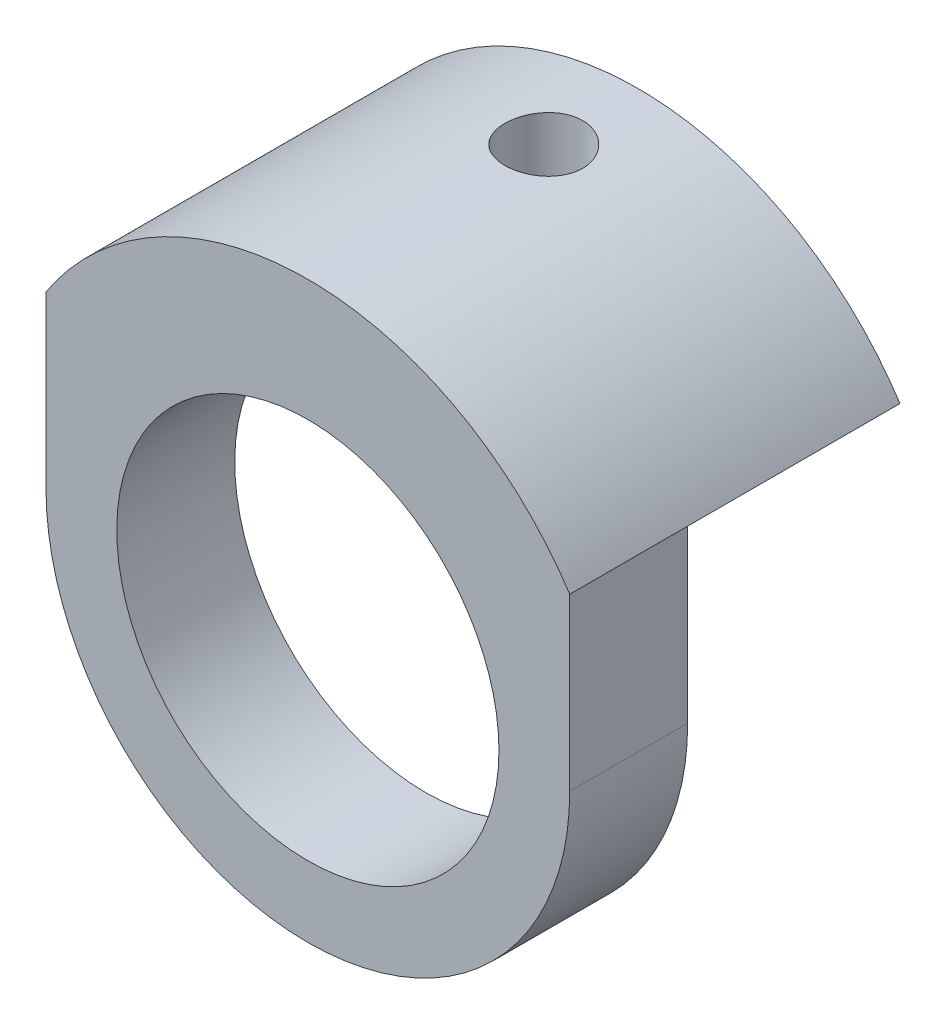
SolidWorks part; units mm, degrees
ref_plane "Front Plane" through (0, 0, 0) normal (0, 0, 1) x (1, 0, 0)
ref_plane "Top Plane" through (0, 0, 0) normal (0, 1, 0) x (1, 0, 0)
ref_plane "Right Plane" through (0, 0, 0) normal (1, 0, 0) x (0, 0, -1)
sketch "Sketch1" plane through (0, 0, 0) normal (0, 0, 1) x (1, 0, 0)
  line L0 (-11.1, 0) -> (11.1, 0)
  line L1 (-11.1, 0) -> (-11.1, 7.2355)
  line L2 (11.1, 0) -> (11.1, 7.2355)
  circle A0 centre (0, 0) radius 8.1
  circle A1 centre (0, 0) radius 13.25
  circle A2 centre (0, 0) radius 11.1
  dimension "16.2" = 16.2
  dimension "D2" = 26.5
  dimension "D3" = 3
extrude "Boss-Extrude1" add sketch "Sketch1" along normal blind 14 contours L0 A2 A0 | A2 L2 A1 L1 | L0 A2 A0
sketch "Sketch2" plane through (-11.1, 0, 0) normal (-1, 0, 0) x (0, 0, 1)
  line L0 (14, 0) -> (14, 7.2355) construction
  line L1 (0, 7.2355) -> (9, 7.2355)
  line L2 (0, 7.2355) -> (0, -11.1)
  line L3 (0, -11.1) -> (9, -11.1)
  line L4 (9, 7.2355) -> (9, -11.1)
  dimension "D1" = 5
extrude "Cut-Extrude1" cut sketch "Sketch2" against normal up to surface (22.2 mm away) up to face at (11.1, 3.6178, 7)
sketch "Sketch3" plane through (0, 7.2355, 0) normal (0, -1, 0) x (1, 0, 0)
  line L0 (-3.6411, 0) -> (3.6411, 0) construction
  circle A0 centre (0, 4) radius 1.65
  dimension "D1" = 3.3
  dimension "D2" = 4
extrude "Cut-Extrude2" cut sketch "Sketch3" against normal up to surface (5.9114 mm away)
sketch "Sketch4" plane through (0, 7.2355, 0) normal (0, -1, 0) x (1, 0, 0)
  line L0 (-3.6411, 0) -> (3.6411, 0) construction
  line L1 (1.6166, 6.8) -> (-1.6166, 6.8)
  line L2 (-1.6166, 6.8) -> (-3.2332, 4)
  line L3 (-3.2332, 4) -> (-1.6166, 1.2)
  line L4 (-1.6166, 1.2) -> (1.6166, 1.2)
  line L5 (1.6166, 1.2) -> (3.2332, 4)
  line L6 (3.2332, 4) -> (1.6166, 6.8)
  circle A0 centre (0, 4) radius 2.8 construction
  dimension "D1" = 5.6
extrude "Cut-Extrude3" cut sketch "Sketch4" against normal blind 3
